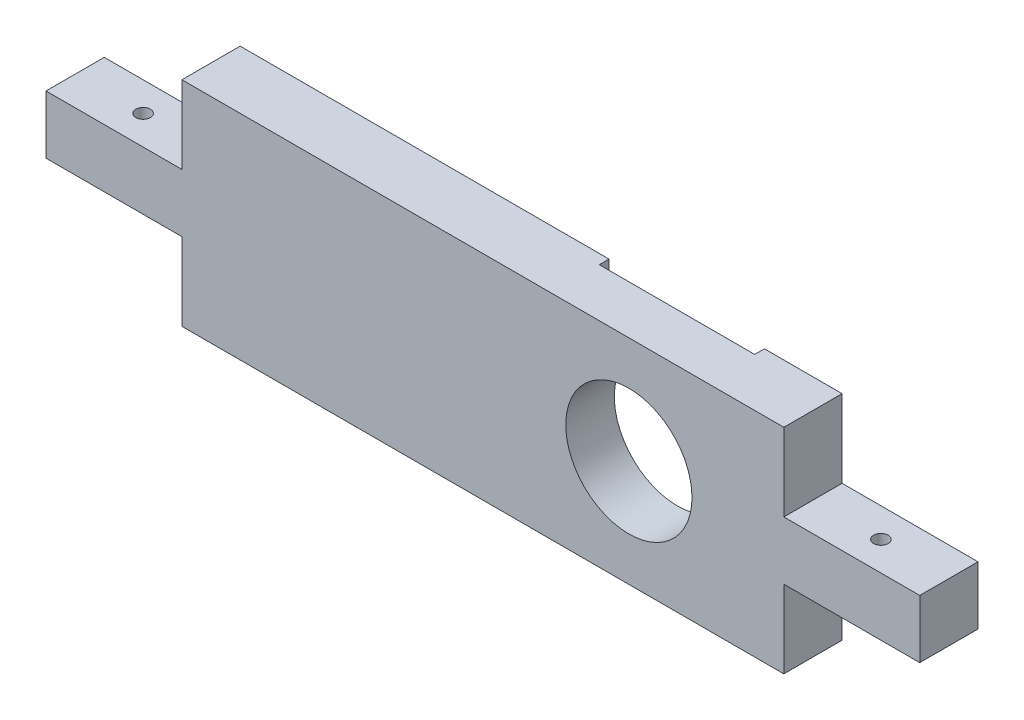
SolidWorks part; units mm, degrees
material "Oak"
ref_plane "Front" through (0, 0, 0) normal (0, 0, 1) x (1, 0, 0)
ref_plane "Top" through (0, 0, 0) normal (0, 1, 0) x (1, 0, 0)
ref_plane "Right" through (0, 0, 0) normal (1, 0, 0) x (0, 0, -1)
sketch "Sketch2" plane through (0, 0, 0) normal (0, 0, 1) x (1, 0, 0)
  line L1 (0, 0) -> (571.5, 0)
  line L2 (0, 0) -> (0, 139.7)
  line L3 (0, 139.7) -> (571.5, 139.7)
  line L4 (571.5, 0) -> (571.5, 139.7)
  dimension "D1" = 139.7
  dimension "D2" = 571.5
extrude "Boss-Extrude2" add sketch "Sketch2" along normal blind 38.1
sketch "Sketch3" plane through (0, 0, 38.1) normal (0, 0, 1) x (1, 0, 0)
  line L0 (0, 88.9) -> (88.9, 88.9)
  line L1 (0, 139.7) -> (0, 0) construction
  line L2 (88.9, 88.9) -> (88.9, 139.7)
  line L3 (571.5, 139.7) -> (0, 139.7) construction
  line L4 (88.9, 139.7) -> (0, 139.7)
  line L5 (0, 139.7) -> (0, 88.9)
  line L6 (0, 69.85) -> (571.5, 69.85) construction
  line L7 (571.5, 0) -> (571.5, 139.7) construction
  line L8 (285.75, 139.7) -> (285.75, 0) construction
  line L9 (0, 0) -> (571.5, 0) construction
  line L10 (571.5, 139.7) -> (571.5, 88.9)
  line L11 (482.6, 88.9) -> (482.6, 139.7)
  line L12 (571.5, 88.9) -> (482.6, 88.9)
  line L13 (482.6, 139.7) -> (571.5, 139.7)
  line L14 (571.5, 0) -> (571.5, 50.8)
  line L15 (571.5, 50.8) -> (482.6, 50.8)
  line L16 (482.6, 0) -> (571.5, 0)
  line L17 (482.6, 50.8) -> (482.6, 0)
  line L18 (88.9, 50.8) -> (88.9, 0)
  line L19 (88.9, 0) -> (0, 0)
  line L20 (0, 0) -> (0, 50.8)
  line L21 (0, 50.8) -> (88.9, 50.8)
  dimension "D1" = 50.8
  dimension "D2" = 88.9
extrude "Cut-Extrude1" cut sketch "Sketch3" against normal through all
sketch "Sketch4" plane through (0, 0, 38.1) normal (0, 0, 1) x (1, 0, 0)
  line L0 (571.5, 50.8) -> (571.5, 88.9) construction
  line L1 (482.6, 139.7) -> (88.9, 139.7) construction
  circle A0 centre (381.2476, 69.85) radius 41.275
  dimension "D3" = 82.55
  dimension "D1" = 69.85
  dimension "D2" = 190.2524
extrude "Cut-Extrude2" cut sketch "Sketch4" against normal through all
sketch "Sketch5" plane through (0, 50.8, 0) normal (0, -1, 0) x (-1, 0, 0)
  line L0 (-88.9, -38.1) -> (0, -38.1) construction
  line L1 (0, 0) -> (0, -38.1) construction
  circle A0 centre (-44.45, -19.05) radius 4.7625
  dimension "D3" = 9.525
  dimension "D1" = 19.05
  dimension "D2" = 44.45
extrude "Cut-Extrude3" cut sketch "Sketch5" against normal through all
sketch "Sketch6" plane through (0, 50.8, 0) normal (0, -1, 0) x (1, 0, 0)
  line L0 (571.5, 38.1) -> (482.6, 38.1) construction
  line L1 (571.5, 0) -> (571.5, 38.1) construction
  circle A0 centre (527.05, 19.05) radius 4.7625
  dimension "D3" = 9.525
  dimension "D1" = 19.05
  dimension "D2" = 44.45
extrude "Cut-Extrude4" cut sketch "Sketch6" against normal through all
sketch "Sketch7" plane through (0, 0, 0) normal (0, -1, 0) x (1, 0, 0)
  line L0 (88.9, 0) -> (482.6, 0) construction
  line L1 (330.2, 0) -> (431.8, 0)
  line L2 (330.2, 0) -> (330.2, 6.35)
  line L3 (330.2, 6.35) -> (431.8, 6.35)
  line L4 (431.8, 0) -> (431.8, 6.35)
  line L5 (381, 6.35) -> (381, -27.3823) construction
  line L6 (482.6, 0) -> (482.6, 38.1) construction
  dimension "D1" = 6.35
  dimension "D2" = 101.6
  dimension "D3" = 101.6
extrude "Cut-Extrude5" cut sketch "Sketch7" against normal through all
